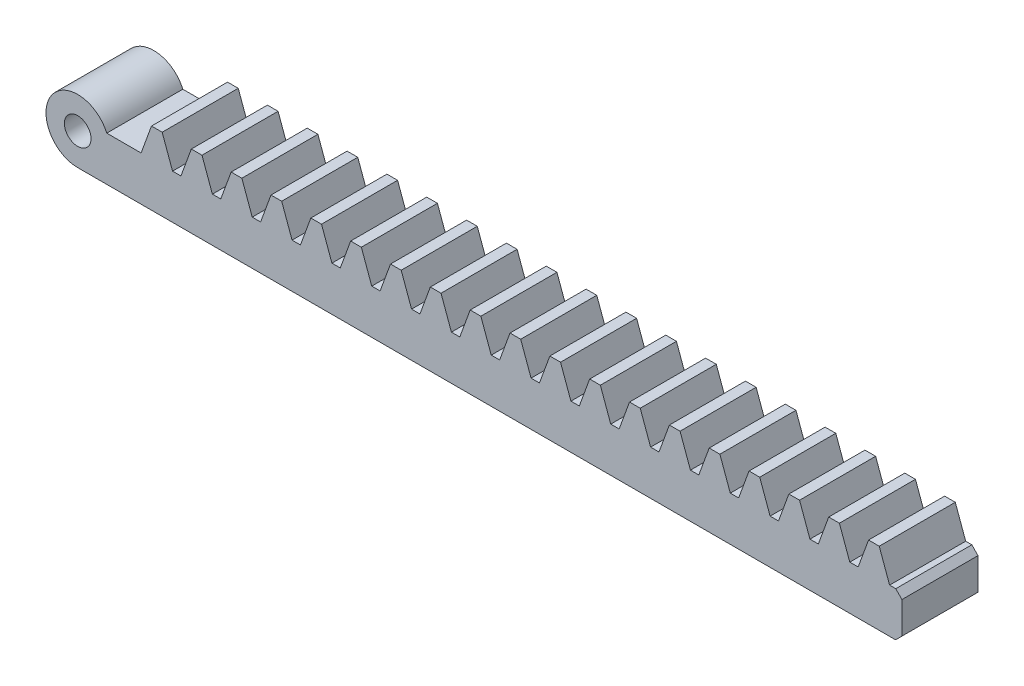
SolidWorks part; units mm, degrees
ref_plane "前视基准面" through (0, 0, 0) normal (0, 0, 1) x (1, 0, 0)
ref_plane "上视基准面" through (0, 0, 0) normal (0, 1, 0) x (1, 0, 0)
ref_plane "右视基准面" through (0, 0, 0) normal (1, 0, 0) x (0, 0, -1)
sketch "草图1" plane through (0, 0, 0) normal (0, 0, 1) x (1, 0, 0)
  line L1 (0, 0) -> (60, 0)
  line L2 (0, 0) -> (0, -3.5)
  line L3 (0, -3.5) -> (60, -3.5)
  line L4 (60, 0) -> (60, -3.5)
  dimension "D1" = 3.5
  dimension "L" = 60
extrude "拉伸1" add sketch "草图1" along normal blind 6
sketch "草图2" plane through (0, 0, 6) normal (0, 0, 1) x (1, 0, 0)
  line L0 (0, 0) -> (0.8189, 2.25)
  line L1 (0.8189, 2.25) -> (1.6618, 2.25)
  line L2 (1.6618, 2.25) -> (2.4807, 0)
  line L3 (60, 0) -> (0, 0) construction
  line L4 (0, 0) -> (2.4807, 0)
  line L5 (0.455, 1.25) -> (2.0258, 1.25) construction
  dimension "D2" = 70
  dimension "alpha" = 110
  dimension "ha" = 1
  dimension "hf" = 1.25
  dimension "S" = 1.5708
extrude "拉伸2" add sketch "草图2" against normal up to surface (6 mm away) up to face at (30, -1.75, 0)
pattern_linear "阵列(线性)1" count 19 spacing 3.1416 along (1, 0, 0) of "拉伸2"
sketch "草图3" plane through (0, 0, 0) normal (0, 0, -1) x (-1, 0, 0)
  line L0 (0, -3.5) -> (-60, -3.5) construction
  line L1 (-3.1416, 0) -> (-2.4807, 0) construction
  line L6 (-32.3969, -1) -> (49967.6031, -1) construction
  line L10 (5, -3.5) -> (0, -3.5)
  line L11 (0, -3.5) -> (0, 0)
  line L12 (0, 0) -> (2.7087, 0)
  circle A2 centre (5, -1) radius 1.05
  arc A3 (5, -3.5) -> (2.7087, 0) centre (5, -1) ccw
  dimension "D1" = 5
  dimension "D4" = 2.1
  dimension "D5" = 2.5
  dimension "D3" = 2.5
sketch "草图4" plane through (0, 0, 0) normal (-1, 0, 0) x (0, 0, 1)
  line L1 (6, 0) -> (0, 0)
  line L2 (6, 0) -> (6, -3.5)
  line L3 (6, -3.5) -> (0, -3.5)
  line L4 (0, 0) -> (0, -3.5)
extrude "凸台-拉伸1" add sketch "草图3" against normal blind 6
sketch "草图5" plane through (0, 0, 0) normal (0, 0, -1) x (-1, 0, 0)
  line L0 (-59.5147, 0) -> (-60, -0.5)
  line L1 (-60, -3.5) -> (-60, 0) construction
  line L2 (-60, -0.5) -> (-60, 0)
  line L3 (-60, 0) -> (-59.5147, 0)
  line L4 (-60, -3.5) -> (-60, -3)
  line L5 (-60, -3) -> (-59.5, -3.5)
  line L6 (5, -3.5) -> (-60, -3.5) construction
  line L7 (-59.5, -3.5) -> (-60, -3.5)
  line L8 (-60, 0) -> (-59.0294, 0) construction
  point P10 (-59.7424, -3.5)
  point P14 (-59.39, -3.5)
  point P15 (0, 0)
  point P16 (-59.5147, 0)
  dimension "D1" = 0.5
  dimension "D2" = 0.5
  dimension "D3" = 45
extrude "切除-拉伸2" cut sketch "草图5" against normal blind 6
equation "\"d\"=\"S@草图2\" * 2"
equation "\"z\"= int(  \"L@草图1\" / (  \"S@草图2\" * 2 ) + 0.5 )"
